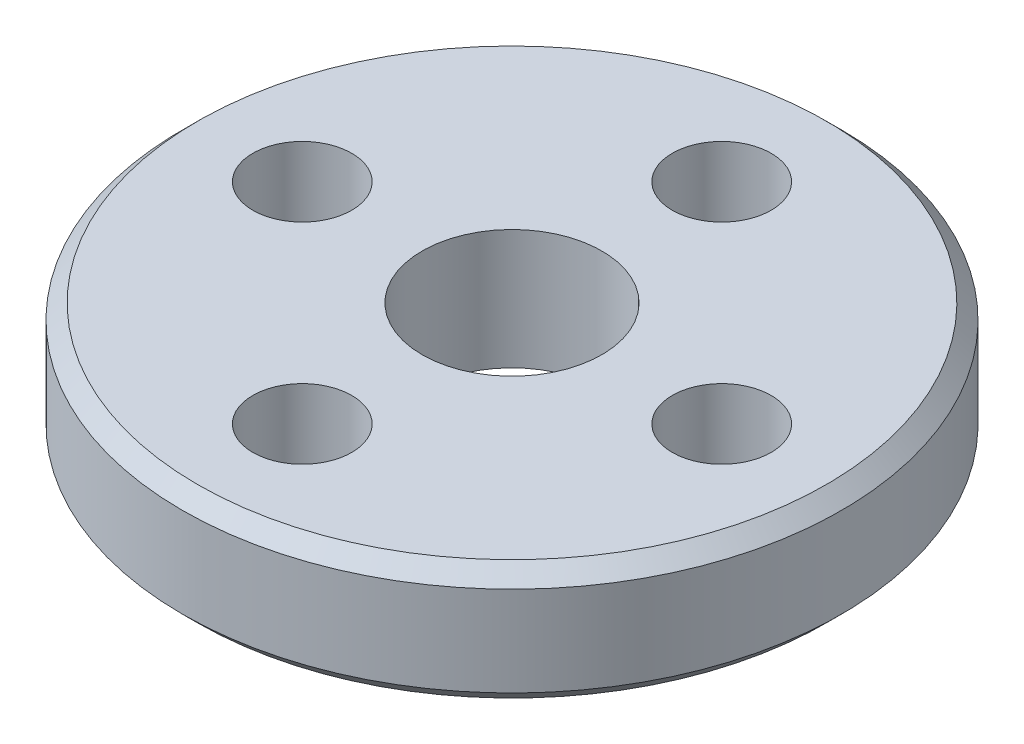
SolidWorks part; units mm, degrees
ref_plane "Plan de face" through (0, 0, 0) normal (0, 0, 1) x (1, 0, 0)
ref_plane "Plan de dessus" through (0, 0, 0) normal (0, 1, 0) x (1, 0, 0)
ref_plane "Plan de droite" through (0, 0, 0) normal (1, 0, 0) x (0, 0, -1)
sketch "Esquisse1" plane through (0, 0, 0) normal (0, 1, 0) x (1, 0, 0)
  circle A0 centre (0, 0) radius 11
  circle A1 centre (0, 0) radius 7 construction
  circle A2 centre (0, 7) radius 1.65
  circle A3 centre (7, 0) radius 1.65
  circle A4 centre (0, -7) radius 1.65
  circle A5 centre (-7, 0) radius 1.65
  circle A6 centre (0, 0) radius 3
  dimension "D1" = 22
  dimension "D2" = 14
  dimension "D3" = 3.3
  dimension "D5" = 6
  dimension "D4" = 4
extrude "Boss.-Extru.1" add sketch "Esquisse1" along normal blind 4
chamfer "Chanfrein1" distance 0.5 angle 45 2 edges at (0, 0, 11) (0, 4, 11)
